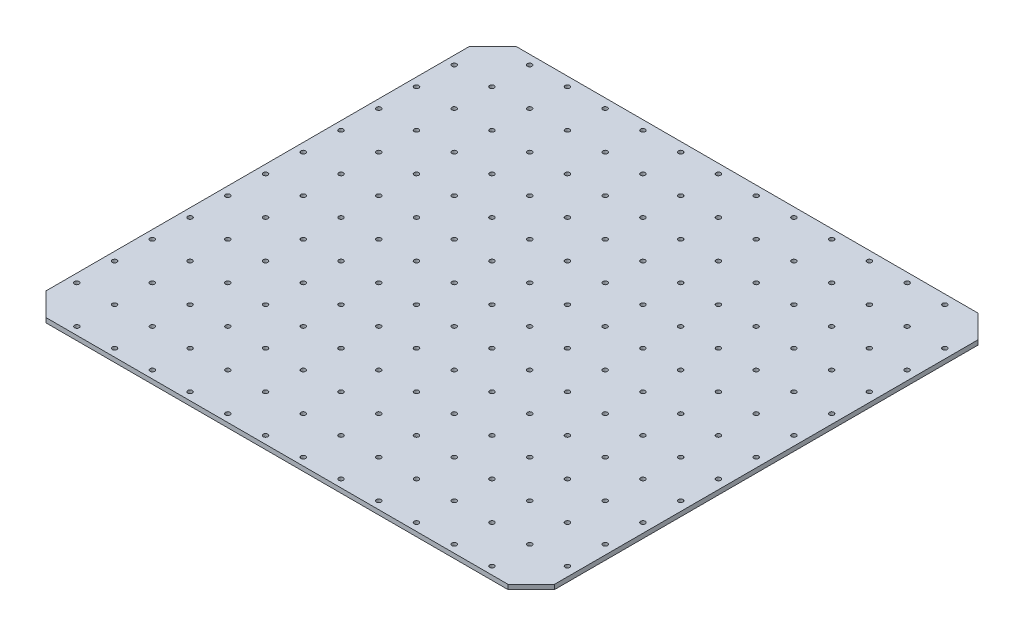
SolidWorks part; units mm, degrees
ref_plane "Front Plane" through (0, 0, 0) normal (0, 0, 1) x (1, 0, 0)
ref_plane "Top Plane" through (0, 0, 0) normal (0, 1, 0) x (1, 0, 0)
ref_plane "Right Plane" through (0, 0, 0) normal (1, 0, 0) x (0, 0, -1)
sketch "Sketch3" plane through (0, 0, 0) normal (0, 1, 0) x (1, 0, 0)
  line L0 (-289.1077, -12.0015) -> (-289.1077, 262.9985)
  line L1 (-289.1077, 262.9985) -> (-274.1077, 277.9985)
  line L2 (-274.1077, 277.9985) -> (25.8923, 277.9985)
  line L3 (25.8923, 277.9985) -> (40.8923, 262.9985)
  line L4 (40.8923, 262.9985) -> (40.8923, -12.0015)
  line L5 (40.8923, -12.0015) -> (25.8923, -27.0015)
  line L6 (25.8923, -27.0015) -> (-274.1077, -27.0015)
  line L7 (-274.1077, -27.0015) -> (-289.1077, -12.0015)
  line L8 (-274.1077, -31.4199) -> (-274.1077, 49968.5801) construction
  line L9 (25.8923, -27.0605) -> (25.8923, 49972.9395) construction
  line L10 (-289.1667, 262.9985) -> (49710.8333, 262.9985) construction
  dimension "D1" = 300
  dimension "D2" = 275
  dimension "D3" = 300
  dimension "D4" = 275
  dimension "D5" = 15
  dimension "D6" = 15
  dimension "D7" = 15
  dimension "D8" = 15
  dimension "D9" = 15
extrude "Boss-Extrude1" add sketch "Sketch3" along normal blind 3
hole_wizard "Ø3.0mm Dowel Slot3" positions "Sketch8" profile "Sketch9" size "Ø3.0" standard "ANSI Metric" slot yes
sketch "Sketch8" plane through (0, 3, 0) normal (0, 1, 0) x (1, 0, 0)
  line L0 (-274.1077, -27.0015) -> (25.8923, -27.0015) construction
  line L1 (-289.1077, 262.9985) -> (-289.1077, -12.0015) construction
  point P0 (-259.1077, -22.0015)
  point P11 (-234.6077, -22.0015)
  point P12 (-210.1077, -22.0015)
  point P13 (-185.6077, -22.0015)
  point P14 (-161.1077, -22.0015)
  point P15 (-136.6077, -22.0015)
  point P16 (-112.1077, -22.0015)
  point P17 (-87.6077, -22.0015)
  point P18 (-63.1077, -22.0015)
  point P19 (-38.6077, -22.0015)
  point P20 (-14.1077, -22.0015)
  point P21 (10.3923, -22.0015)
  point P30 (-259.1077, 2.4985)
  point P31 (-259.1077, 26.9985)
  point P32 (-259.1077, 51.4985)
  point P33 (-259.1077, 75.9985)
  point P34 (-259.1077, 100.4985)
  point P35 (-259.1077, 124.9985)
  point P36 (-259.1077, 149.4985)
  point P37 (-259.1077, 173.9985)
  point P38 (-259.1077, 198.4985)
  point P39 (-259.1077, 222.9985)
  point P40 (-259.1077, 247.4985)
  point P41 (-259.1077, 271.9985)
  point P60 (-234.6077, 2.4985)
  point P61 (-210.1077, 2.4985)
  point P62 (-185.6077, 2.4985)
  point P63 (-161.1077, 2.4985)
  point P64 (-136.6077, 2.4985)
  point P65 (-112.1077, 2.4985)
  point P66 (-87.6077, 2.4985)
  point P67 (-63.1077, 2.4985)
  point P68 (-38.6077, 2.4985)
  point P69 (-14.1077, 2.4985)
  point P70 (10.3923, 2.4985)
  point P71 (-234.6077, 26.9985)
  point P72 (-210.1077, 26.9985)
  point P73 (-185.6077, 26.9985)
  point P74 (-161.1077, 26.9985)
  point P75 (-136.6077, 26.9985)
  point P76 (-112.1077, 26.9985)
  point P77 (-87.6077, 26.9985)
  point P78 (-63.1077, 26.9985)
  point P79 (-38.6077, 26.9985)
  point P80 (-14.1077, 26.9985)
  point P81 (10.3923, 26.9985)
  point P82 (-234.6077, 51.4985)
  point P83 (-210.1077, 51.4985)
  point P84 (-185.6077, 51.4985)
  point P85 (-161.1077, 51.4985)
  point P86 (-136.6077, 51.4985)
  point P87 (-112.1077, 51.4985)
  point P88 (-87.6077, 51.4985)
  point P89 (-63.1077, 51.4985)
  point P90 (-38.6077, 51.4985)
  point P91 (-14.1077, 51.4985)
  point P92 (10.3923, 51.4985)
  point P93 (-234.6077, 75.9985)
  point P94 (-210.1077, 75.9985)
  point P95 (-185.6077, 75.9985)
  point P96 (-161.1077, 75.9985)
  point P97 (-136.6077, 75.9985)
  point P98 (-112.1077, 75.9985)
  point P99 (-87.6077, 75.9985)
  point P100 (-63.1077, 75.9985)
  point P101 (-38.6077, 75.9985)
  point P102 (-14.1077, 75.9985)
  point P103 (10.3923, 75.9985)
  point P104 (-234.6077, 100.4985)
  point P105 (-210.1077, 100.4985)
  point P106 (-185.6077, 100.4985)
  point P107 (-161.1077, 100.4985)
  point P108 (-136.6077, 100.4985)
  point P109 (-112.1077, 100.4985)
  point P110 (-87.6077, 100.4985)
  point P111 (-63.1077, 100.4985)
  point P112 (-38.6077, 100.4985)
  point P113 (-14.1077, 100.4985)
  point P114 (10.3923, 100.4985)
  point P115 (-234.6077, 124.9985)
  point P116 (-210.1077, 124.9985)
  point P117 (-185.6077, 124.9985)
  point P118 (-161.1077, 124.9985)
  point P119 (-136.6077, 124.9985)
  point P120 (-112.1077, 124.9985)
  point P121 (-87.6077, 124.9985)
  point P122 (-63.1077, 124.9985)
  point P123 (-38.6077, 124.9985)
  point P124 (-14.1077, 124.9985)
  point P125 (10.3923, 124.9985)
  point P126 (-234.6077, 149.4985)
  point P127 (-210.1077, 149.4985)
  point P128 (-185.6077, 149.4985)
  point P129 (-161.1077, 149.4985)
  point P130 (-136.6077, 149.4985)
  point P131 (-112.1077, 149.4985)
  point P132 (-87.6077, 149.4985)
  point P133 (-63.1077, 149.4985)
  point P134 (-38.6077, 149.4985)
  point P135 (-14.1077, 149.4985)
  point P136 (10.3923, 149.4985)
  point P137 (-234.6077, 173.9985)
  point P138 (-210.1077, 173.9985)
  point P139 (-185.6077, 173.9985)
  point P140 (-161.1077, 173.9985)
  point P141 (-136.6077, 173.9985)
  point P142 (-112.1077, 173.9985)
  point P143 (-87.6077, 173.9985)
  point P144 (-63.1077, 173.9985)
  point P145 (-38.6077, 173.9985)
  point P146 (-14.1077, 173.9985)
  point P147 (10.3923, 173.9985)
  point P148 (-234.6077, 198.4985)
  point P149 (-210.1077, 198.4985)
  point P150 (-185.6077, 198.4985)
  point P151 (-161.1077, 198.4985)
  point P152 (-136.6077, 198.4985)
  point P153 (-112.1077, 198.4985)
  point P154 (-87.6077, 198.4985)
  point P155 (-63.1077, 198.4985)
  point P156 (-38.6077, 198.4985)
  point P157 (-14.1077, 198.4985)
  point P158 (10.3923, 198.4985)
  point P159 (-234.6077, 222.9985)
  point P160 (-210.1077, 222.9985)
  point P161 (-185.6077, 222.9985)
  point P162 (-161.1077, 222.9985)
  point P163 (-136.6077, 222.9985)
  point P164 (-112.1077, 222.9985)
  point P165 (-87.6077, 222.9985)
  point P166 (-63.1077, 222.9985)
  point P167 (-38.6077, 222.9985)
  point P168 (-14.1077, 222.9985)
  point P169 (10.3923, 222.9985)
  point P170 (-234.6077, 247.4985)
  point P171 (-210.1077, 247.4985)
  point P172 (-185.6077, 247.4985)
  point P173 (-161.1077, 247.4985)
  point P174 (-136.6077, 247.4985)
  point P175 (-112.1077, 247.4985)
  point P176 (-87.6077, 247.4985)
  point P177 (-63.1077, 247.4985)
  point P178 (-38.6077, 247.4985)
  point P179 (-14.1077, 247.4985)
  point P180 (10.3923, 247.4985)
  point P181 (-234.6077, 271.9985)
  point P182 (-210.1077, 271.9985)
  point P183 (-185.6077, 271.9985)
  point P184 (-161.1077, 271.9985)
  point P185 (-136.6077, 271.9985)
  point P186 (-112.1077, 271.9985)
  point P187 (-87.6077, 271.9985)
  point P188 (-63.1077, 271.9985)
  point P189 (-38.6077, 271.9985)
  point P190 (-14.1077, 271.9985)
  point P191 (10.3923, 271.9985)
  point P224 (34.8923, 2.4985)
  point P225 (34.8923, 26.9985)
  point P226 (34.8923, 51.4985)
  point P227 (34.8923, 75.9985)
  point P228 (34.8923, 100.4985)
  point P229 (34.8923, 124.9985)
  point P230 (34.8923, 149.4985)
  point P231 (34.8923, 173.9985)
  point P232 (34.8923, 198.4985)
  point P233 (34.8923, 222.9985)
  point P234 (34.8923, 247.4985)
  point P254 (-283.6077, 2.4985)
  point P255 (-283.6077, 26.9985)
  point P256 (-283.6077, 51.4985)
  point P257 (-283.6077, 75.9985)
  point P258 (-283.6077, 100.4985)
  point P259 (-283.6077, 124.9985)
  point P260 (-283.6077, 149.4985)
  point P261 (-283.6077, 173.9985)
  point P262 (-283.6077, 198.4985)
  point P263 (-283.6077, 222.9985)
  point P264 (-283.6077, 247.4985)
  dimension "D1" = 5
  dimension "D2" = 30
  dimension "D6" = 2
  dimension "D3" = 12
  dimension "D4" = 13
  dimension "D5" = 13
  dimension "D7" = 2
sketch "Sketch9" plane through (-259.1077, 3, 22.0015) normal (1, 0, 0) x (0, 0, 1)
  line L0 (0, 0) -> (0, 6.1013)
  line L1 (0, 6.1013) -> (1.5, 5.2)
  line L2 (1.5, 5.2) -> (1.5, 0)
  line L5 (1.5, 0) -> (0, 0)
  line L10 (0, 6.1013) -> (-1.5, 5.2) construction
  line L11 (0, -6.35) -> (0, 107.95) construction
  dimension "Hole Dia." = 3
  dimension "Hole Depth" = 5.2
  dimension "Drill Angle" = 118
